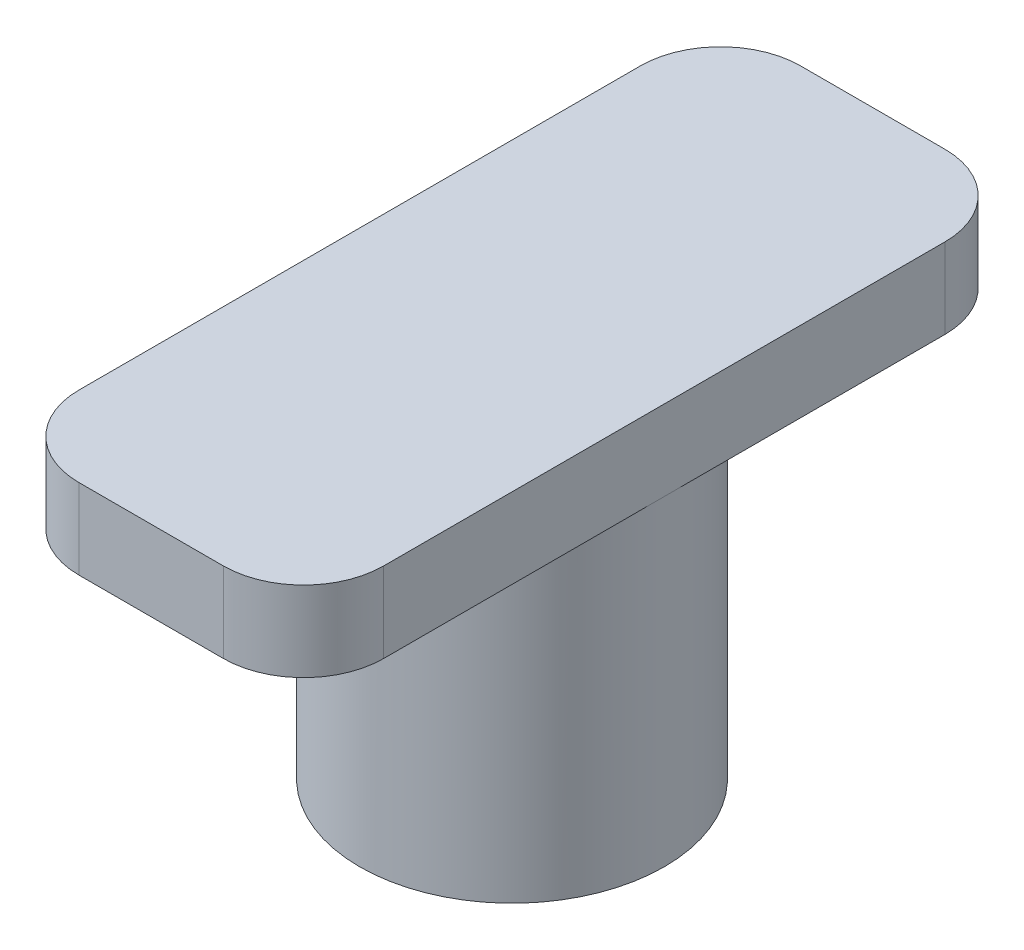
SolidWorks part; units mm, degrees
ref_plane "Front Plane" through (0, 0, 0) normal (0, 0, 1) x (1, 0, 0)
ref_plane "Top Plane" through (0, 0, 0) normal (0, 1, 0) x (1, 0, 0)
ref_plane "Right Plane" through (0, 0, 0) normal (1, 0, 0) x (0, 0, -1)
sketch "Sketch1" plane through (0, 0, 0) normal (0, 1, 0) x (1, 0, 0)
  circle A0 centre (0, 0) radius 38
extrude "Boss-Extrude1" add sketch "Sketch1" along normal blind 80
sketch "Sketch2" plane through (0, 0, 0) normal (0, -1, 0) x (1, 0, 0)
  circle A0 centre (0, 0) radius 29
extrude "Cut-Extrude1" cut sketch "Sketch2" against normal blind 75
sketch "Sketch3" plane through (0, 80, 0) normal (0, 1, 0) x (1, 0, 0)
  line L1 (18, -90) -> (-18, -90)
  line L2 (38, -70) -> (38, 70)
  line L3 (18, 90) -> (-18, 90)
  line L4 (-38, -70) -> (-38, 70)
  line L5 (38, -90) -> (-38, 90) construction
  line L6 (38, 90) -> (-38, -90) construction
  arc A1 (18, -90) -> (38, -70) centre (18, -70) ccw
  arc A2 (-18, -90) -> (-38, -70) centre (-18, -70) cw
  arc A3 (38, 70) -> (18, 90) centre (18, 70) ccw
  arc A4 (-18, 90) -> (-38, 70) centre (-18, 70) ccw
  point P0 (0, 0)
  dimension "D1" = 20
extrude "Boss-Extrude2" add sketch "Sketch3" along normal blind 20 contours L2 A3 L3 A4 L4 A2 L1 A1
